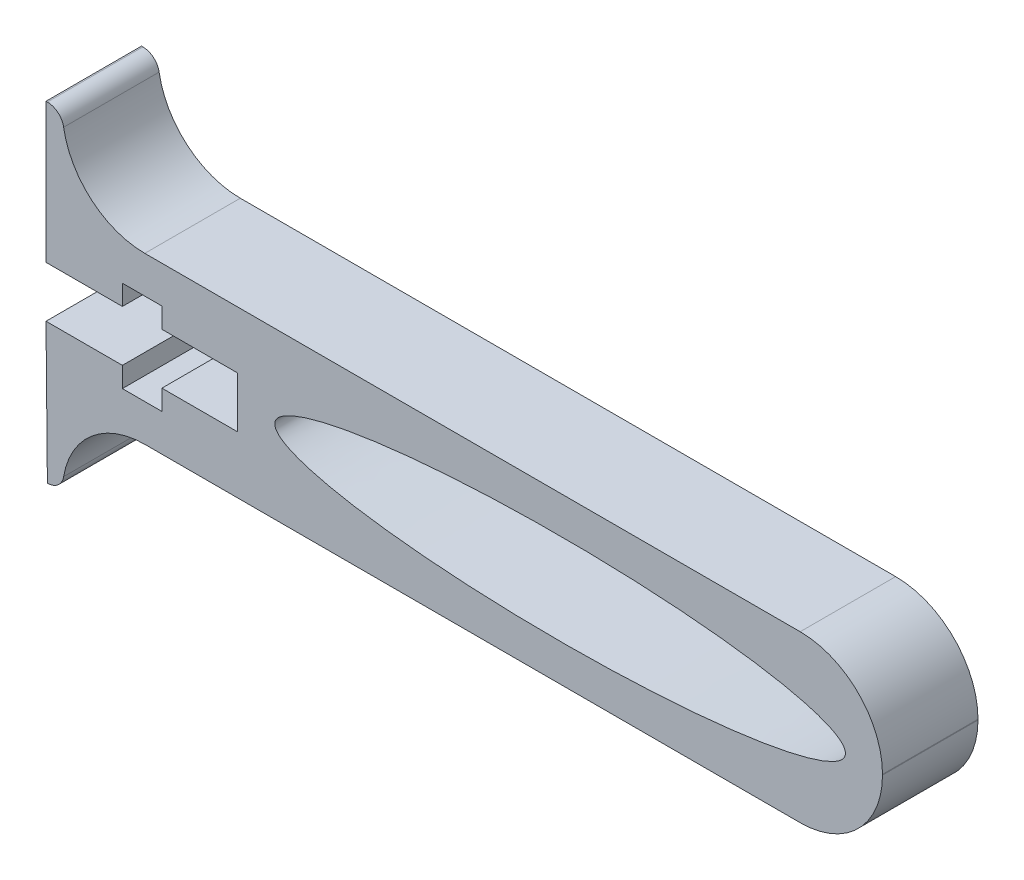
SolidWorks part; units mm, degrees
ref_plane "Front Plane" through (0, 0, 0) normal (0, 0, 1) x (1, 0, 0)
ref_plane "Top Plane" through (0, 0, 0) normal (0, 1, 0) x (1, 0, 0)
ref_plane "Right Plane" through (0, 0, 0) normal (1, 0, 0) x (0, 0, -1)
sketch "Sketch1" plane through (0, 0, 0) normal (0, 0, 1) x (1, 0, 0)
  line L0 (-12.4599, 26.5844) -> (-17.0981, 26.5844) construction
  line L1 (-12.4599, 26.5844) -> (-12.4599, 28.1323) construction
  line L2 (-12.4599, 25.0366) -> (-12.4599, 26.5844) construction
  line L3 (-11.2599, 29.3567) -> (-11.2599, 26.5844) construction
  line L4 (-5.455, 26.5844) -> (-17.0981, 26.5844) construction
  line L5 (-11.2599, 23.8122) -> (-11.2599, 26.5844) construction
  line L6 (-10.0599, 29.3567) -> (-12.4599, 29.3567)
  line L7 (-10.0599, 23.8122) -> (-12.4599, 23.8122)
  line L8 (-5.455, 25.0366) -> (-5.455, 28.1323)
  line L9 (-17.0981, 28.1323) -> (-12.4599, 28.1323)
  line L10 (-12.4599, 25.0366) -> (-17.0981, 25.0366)
  line L11 (-12.4599, 25.0366) -> (-12.4599, 23.8122)
  line L12 (-12.4599, 29.3567) -> (-12.4599, 28.1323)
  line L13 (-10.0599, 25.0366) -> (-10.0599, 23.8122)
  line L14 (-10.0599, 28.1323) -> (-5.455, 28.1323)
  line L15 (-10.0599, 25.0366) -> (-5.455, 25.0366)
  line L16 (-10.0599, 29.3567) -> (-10.0599, 28.1323)
  line L17 (-17.0981, 28.1323) -> (-17.0981, 25.0366) construction
  line L18 (-17.0981, 28.1323) -> (-17.0981, 36.6067)
  line L19 (-11.0981, 31.6067) -> (28.7019, 31.6067)
  line L20 (33.7019, 26.6067) -> (33.7019, 26.5622)
  line L21 (28.7019, 21.5622) -> (-11.0981, 21.5622)
  line L22 (-17.0141, 16.5622) -> (-17.0981, 25.0366)
  line L23 (-5.455, 26.5844) -> (33.7019, 26.5844) construction
  line L25 (-17.0981, 36.6067) -> (-17.0141, 36.6067)
  arc A0 (28.7019, 21.5622) -> (33.7019, 26.5622) centre (28.7019, 26.5622) ccw
  arc A1 (28.7019, 31.6067) -> (33.7019, 26.6067) centre (28.7019, 26.6067) cw
  arc A2 (-16.0281, 35.7733) -> (-11.0981, 31.6067) centre (-11.0981, 36.6067) ccw
  arc A3 (-17.0141, 36.6067) -> (-16.0281, 35.7733) centre (-17.0141, 35.6067) cw
  arc A4 (-17.0141, 16.5622) -> (-16.0281, 17.3955) centre (-17.0141, 17.5622) ccw
  arc A5 (-16.0281, 17.3955) -> (-11.0981, 21.5622) centre (-11.0981, 16.5622) cw
  ellipse E0 centre (14.1235, 26.5844) end of major axis (-3.205, 26.5844) minor radius 2.7722
  point P39 (-16.0981, 36.6067)
  dimension "D6" = 5
  dimension "D11" = 1
  dimension "D1" = 2.4
  dimension "D2" = 1.2244
  dimension "D3" = 4.6382
  dimension "D4" = 2.25
  dimension "D5" = 50.8
  dimension "D7" = 2.25
  dimension "D8" = 2.25
  dimension "D10" = 1
extrude "Boss-Extrude1" add sketch "Sketch1" along normal blind 5.8
